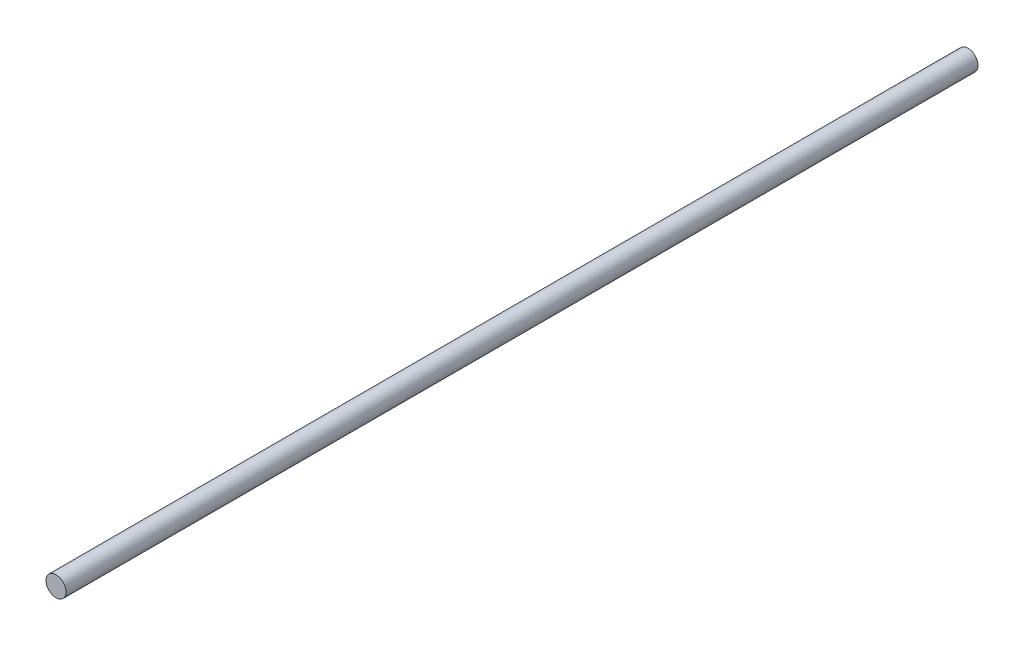
SolidWorks part; units mm, degrees
ref_plane "Alzado" through (0, 0, 0) normal (0, 0, 1) x (1, 0, 0)
ref_plane "Planta" through (0, 0, 0) normal (0, 1, 0) x (1, 0, 0)
ref_plane "Vista lateral" through (0, 0, 0) normal (1, 0, 0) x (0, 0, -1)
sketch "Croquis1" plane through (0, 0, 0) normal (0, 0, 1) x (1, 0, 0)
  circle A0 centre (0, 0) radius 2.75
  dimension "D1" = 5.5
extrude "Saliente-Extruir1" add sketch "Croquis1" along normal mid plane 250
